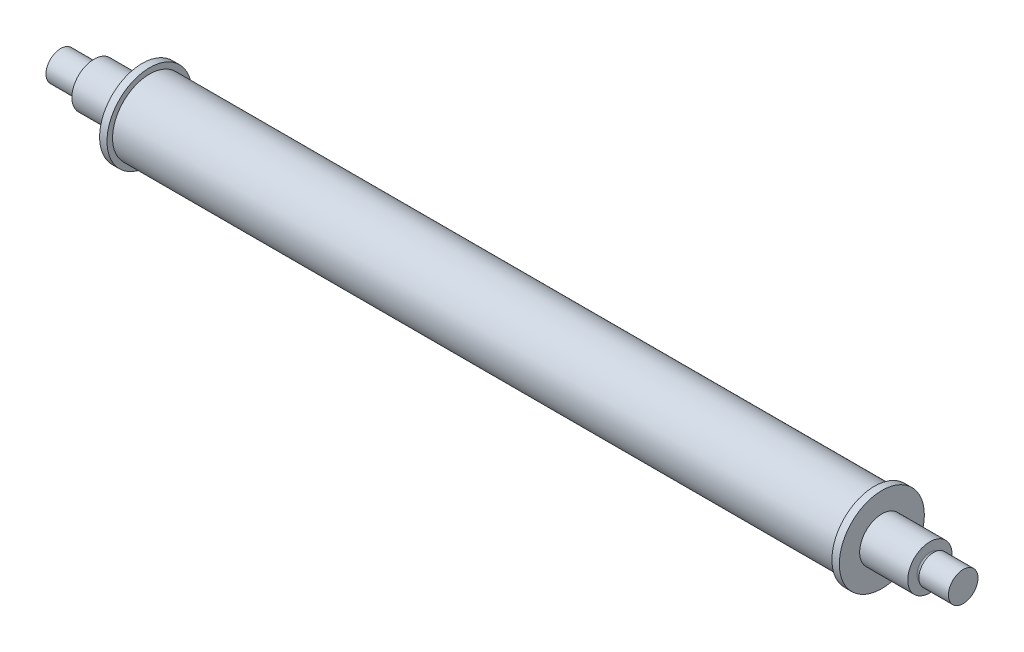
SolidWorks part; units mm, degrees
ref_plane "Front Plane" through (0, 0, 0) normal (0, 0, 1) x (1, 0, 0)
ref_plane "Top Plane" through (0, 0, 0) normal (0, 1, 0) x (1, 0, 0)
ref_plane "Right Plane" through (0, 0, 0) normal (1, 0, 0) x (0, 0, -1)
sketch "Sketch1" plane through (0, 0, 0) normal (0, 0, 1) x (1, 0, 0)
  line L0 (-75.0769, 2.4615) -> (-75.0769, 0)
  line L1 (-75.0769, 0) -> (75.0769, 0)
  line L2 (75.0769, 0) -> (75.0769, 2.4615)
  line L3 (75.0769, 2.4615) -> (70.1538, 2.4615)
  line L4 (70.1538, 2.4615) -> (70.1538, 2.1538)
  line L5 (69.5385, 2.1538) -> (69.5385, 3.6923)
  line L6 (69.5385, 3.6923) -> (61.5385, 3.6923)
  line L7 (61.5385, 3.6923) -> (61.5385, 7.0769)
  line L8 (61.5385, 7.0769) -> (60.3077, 7.0769)
  line L9 (60.3077, 7.0769) -> (60.3077, 6.1538)
  line L10 (60.3077, 6.1538) -> (-60.3077, 6.1538)
  line L11 (-60.3077, 6.1538) -> (-60.3077, 7.0769)
  line L12 (-60.3077, 7.0769) -> (-61.5385, 7.0769)
  line L13 (-61.5385, 7.0769) -> (-61.5385, 3.6923)
  line L14 (-61.5385, 3.6923) -> (-69.5385, 3.6923)
  line L15 (-69.5385, 3.6923) -> (-69.5385, 2.1538)
  line L16 (-70.1538, 2.1538) -> (-70.1538, 2.4615)
  line L17 (-70.1538, 2.4615) -> (-75.0769, 2.4615)
  line L18 (-75.0769, 0) -> (75.0769, 0) construction
  arc A0 (70.1538, 2.1538) -> (69.5385, 2.1538) centre (69.8462, 2.1538) cw
  arc A1 (-69.5385, 2.1538) -> (-70.1538, 2.1538) centre (-69.8462, 2.1538) cw
  dimension "D1" = 8
  dimension "D2" = 8
  dimension "D3" = 4.9231
  dimension "D4" = 2.4615
  dimension "D5" = 4.9231
  dimension "D6" = 150.1538
  dimension "D7" = 120.6154
revolve "Revolve1" add sketch "Sketch1" angle 360 about L18
